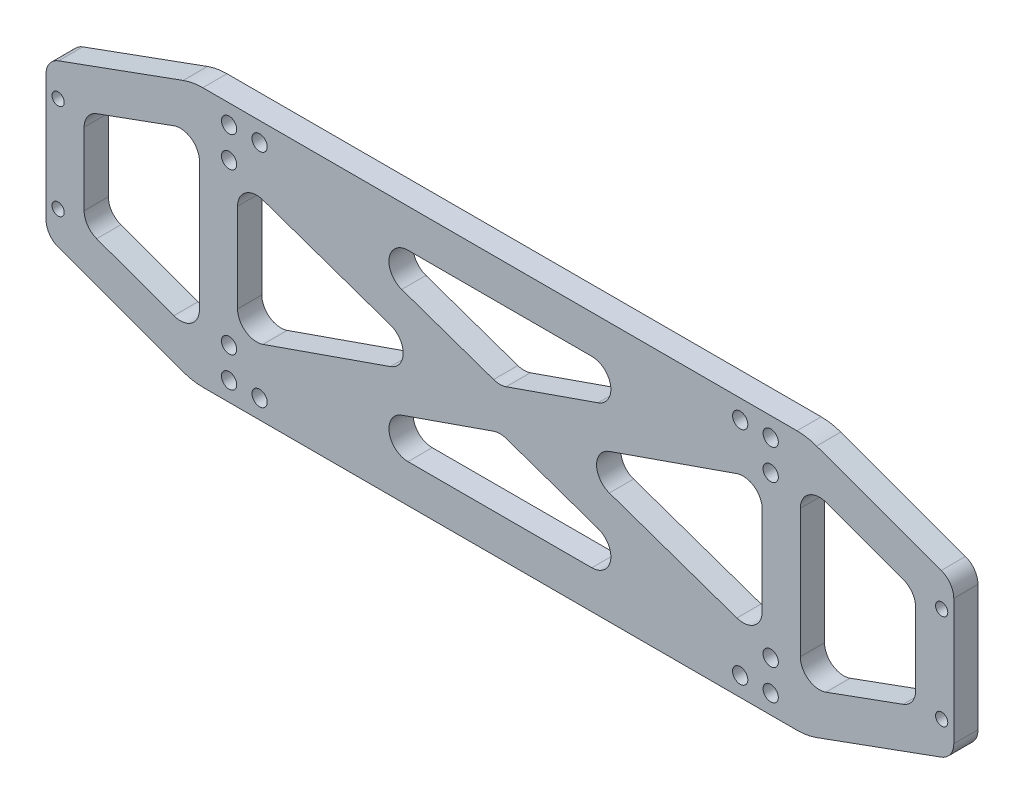
SolidWorks part; units mm, degrees
material "6061 Alloy"
ref_plane "Front Plane" through (0, 0, 0) normal (0, 0, 1) x (1, 0, 0)
ref_plane "Top Plane" through (0, 0, 0) normal (0, 1, 0) x (1, 0, 0)
ref_plane "Right Plane" through (0, 0, 0) normal (1, 0, 0) x (0, 0, -1)
sketch "Sketch1" plane through (0, 0, 0) normal (0, 0, 1) x (1, 0, 0)
  line L0 (80.5353, 34) -> (119, 20)
  line L1 (-119, -20) -> (-80.5353, -34)
  line L2 (-119, -20) -> (-119, 20)
  line L3 (-119, 20) -> (-80.5353, 34)
  line L4 (119, -20) -> (119, 20)
  line L5 (-119, -20) -> (119, 20) construction
  line L6 (-119, 20) -> (119, -20) construction
  line L7 (-80.5353, 34) -> (80.5353, 34)
  line L8 (80.5353, -34) -> (119, -20)
  line L9 (-80.5353, -34) -> (80.5353, -34)
  line L10 (0, -34) -> (0, 34) construction
  line L11 (119, 0) -> (-119, 0) construction
  point P0 (0, 0)
  dimension "D1" = 238
  dimension "D2" = 40
  dimension "D3" = 68
  dimension "D4" = 20
extrude "Boss-Extrude1" add sketch "Sketch1" along normal blind 6.35
hole_wizard "M3 Clearance Hole1" positions "Sketch3" profile "Sketch4" hole size "M3" standard "ANSI Metric"
sketch "Sketch3" plane through (0, 0, 0) normal (0, 0, 1) x (1, 0, 0)
  line L0 (115.825, -12.5) -> (115.825, 12.5)
  line L3 (-115.825, -12.5) -> (-115.825, 12.5)
  line L5 (0, 0) -> (0, 25) construction
  line L7 (119, -20) -> (119, 20) construction
  line L8 (115.825, 0) -> (-115.825, 0) construction
  point P23 (115.825, 12.5)
  point P25 (115.825, -12.5)
  point P27 (-115.825, -12.5)
  point P29 (-115.825, 12.5)
  dimension "D1" = 3.175
  dimension "D2" = 25
sketch "Sketch4" plane through (115.825, 12.5, 0) normal (1, 0, 0) x (0, 1, 0)
  line L0 (0, 0) -> (0, 96.6614)
  line L1 (0, 96.6614) -> (1.6, 95.7)
  line L2 (1.6, 95.7) -> (1.6, 0)
  line L5 (1.6, 0) -> (0, 0)
  line L10 (0, 96.6614) -> (-1.6, 95.7) construction
  line L11 (0, -6.35) -> (0, 107.95) construction
  dimension "Hole Dia." = 3.2
  dimension "Hole Depth" = 95.7
  dimension "Drill Angle" = 118
fillet "Fillet1" radius 5 4 edges at (-119, 20, 3.175) (-119, -20, 3.175) (119, 20, 3.175) (119, -20, 3.175)
fillet "Fillet2" radius 15 4 edges at (-80.5353, -34, 3.175) (80.5353, -34, 3.175) (-80.5353, 34, 3.175) (80.5353, 34, 3.175)
sketch "Sketch5" plane through (0, 0, 0) normal (0, 0, -1) x (-1, 0, 0)
  line L112 (-79.6005, 23.6985) -> (-109, 12.9979)
  line L113 (79.6005, -23.6985) -> (109, -12.9979)
  line L114 (109, -12.9979) -> (109, 12.9979)
  line L115 (77.8904, 24) -> (-77.8904, 24)
  line L116 (109, 12.9979) -> (79.6005, 23.6985)
  line L117 (-109, 12.9979) -> (-109, -12.9979)
  line L118 (-109, -12.9979) -> (-79.6005, -23.6985)
  line L119 (-77.8904, -24) -> (77.8904, -24)
  line L120 (-78.772, 24) -> (-109, 12.9979)
  line L121 (78.772, -24) -> (109, -12.9979)
  line L122 (109, -12.9979) -> (109, 12.9979)
  line L123 (78.772, 24) -> (-78.772, 24)
  line L124 (109, 12.9979) -> (78.772, 24)
  line L125 (-109, 12.9979) -> (-109, -12.9979)
  line L126 (-109, -12.9979) -> (-78.772, -24)
  line L127 (-78.772, -24) -> (78.772, -24)
  arc A47 (77.8904, -24) -> (79.6005, -23.6985) centre (77.8904, -19) ccw
  arc A48 (79.6005, 23.6985) -> (77.8904, 24) centre (77.8904, 19) ccw
  arc A49 (-77.8904, 24) -> (-79.6005, 23.6985) centre (-77.8904, 19) ccw
  arc A50 (-79.6005, -23.6985) -> (-77.8904, -24) centre (-77.8904, -19) ccw
  dimension "D1" = 10
extrude "Cut-Extrude1" cut sketch "Sketch5" against normal through all
sketch "Sketch6" plane through (0, 0, 0) normal (0, 0, -1) x (-1, 0, 0)
  line L0 (78.772, 24) -> (-78.772, 24) construction
  line L1 (-78.772, -24) -> (-68.772, -24)
  line L2 (-78.772, -24) -> (-78.772, 24)
  line L3 (-78.772, 24) -> (-68.772, 24)
  line L4 (-68.772, -24) -> (-68.772, 24)
  line L6 (78.772, -24) -> (68.772, -24)
  line L7 (78.772, -24) -> (78.772, 24)
  line L8 (78.772, 24) -> (68.772, 24)
  line L9 (68.772, -24) -> (68.772, 24)
  dimension "D1" = 10
extrude "Boss-Extrude2" add sketch "Sketch6" against normal up to surface (6.35 mm away) up to face at (0, 0, 6.35)
sketch "Sketch7" plane through (0, 0, 0) normal (0, 0, -1) x (-1, 0, 0)
  line L1 (68.772, 24) -> (-68.772, -24)
extrude "Extrude-Thin1" add sketch "Sketch7" against normal up to surface (6.35 mm away) thin up to face at (0, 0, 6.35) thin type mid plane wall 10
mirror "Mirror1" about plane through (0, 0, 0) normal (1, 0, 0) of "Extrude-Thin1"
hole_wizard "Ø4.0 Reamed" positions "Sketch9" profile "Sketch10" hole size "Ø4.0" standard "ANSI Metric" end condition through all
sketch "Sketch9" plane through (0, 0, 0) normal (0, 0, -1) x (-1, 0, 0)
  line L0 (-71, -29) -> (71, -29) construction
  line L2 (0, 0) -> (0, -29) construction
  line L4 (53.5971, -24) -> (53.5971, -34) construction
  line L5 (77.8904, -34) -> (-77.8904, -34) construction
  line L7 (-71, -29) -> (-71, -21) construction
  point P0 (-71, -29)
  point P2 (-63, -29)
  point P4 (-71, -21)
  point P25 (53.5971, -29)
  dimension "D1" = 142
  dimension "D2" = 8
  dimension "D3" = 8
sketch "Sketch10" plane through (71, -29, 0) normal (1, 0, 0) x (0, 1, 0)
  line L0 (0, 0) -> (0, 6.35)
  line L1 (0, 6.35) -> (2, 6.35)
  line L2 (2, 6.35) -> (2, 0)
  line L5 (2, 0) -> (0, 0)
  line L11 (0, -6.35) -> (0, 107.95) construction
  dimension "Thru Hole Dia." = 4
  dimension "Thru Hole Depth" = 6.35
mirror "Mirror2" about plane through (0, 0, 0) normal (1, 0, 0) of "Ø4.0 Reamed"
mirror "Mirror3" about plane through (0, 0, 0) normal (0, 1, 0) of "Mirror2", "Ø4.0 Reamed"
fillet "Fillet3" radius 5 20 edges at (-109, 12.9979, 3.175) (-109, -12.9979, 3.175) (-78.772, 24, 3.175) (-78.772, -24, 3.175) (-68.772, -18.7043, 3.175) (-68.772, 18.7043, 3.175) (-15.1749, 0, 3.175) (-53.5971, 24, 3.175) (53.5971, 24, 3.175) (0, 5.2957, 3.175) (0, -5.2957, 3.175) (-53.5971, -24, 3.175) (53.5971, -24, 3.175) (15.1749, 0, 3.175) (68.772, -18.7043, 3.175) (68.772, 18.7043, 3.175) (78.772, -24, 3.175) (109, -12.9979, 3.175) (109, 12.9979, 3.175) (78.772, 24, 3.175)
